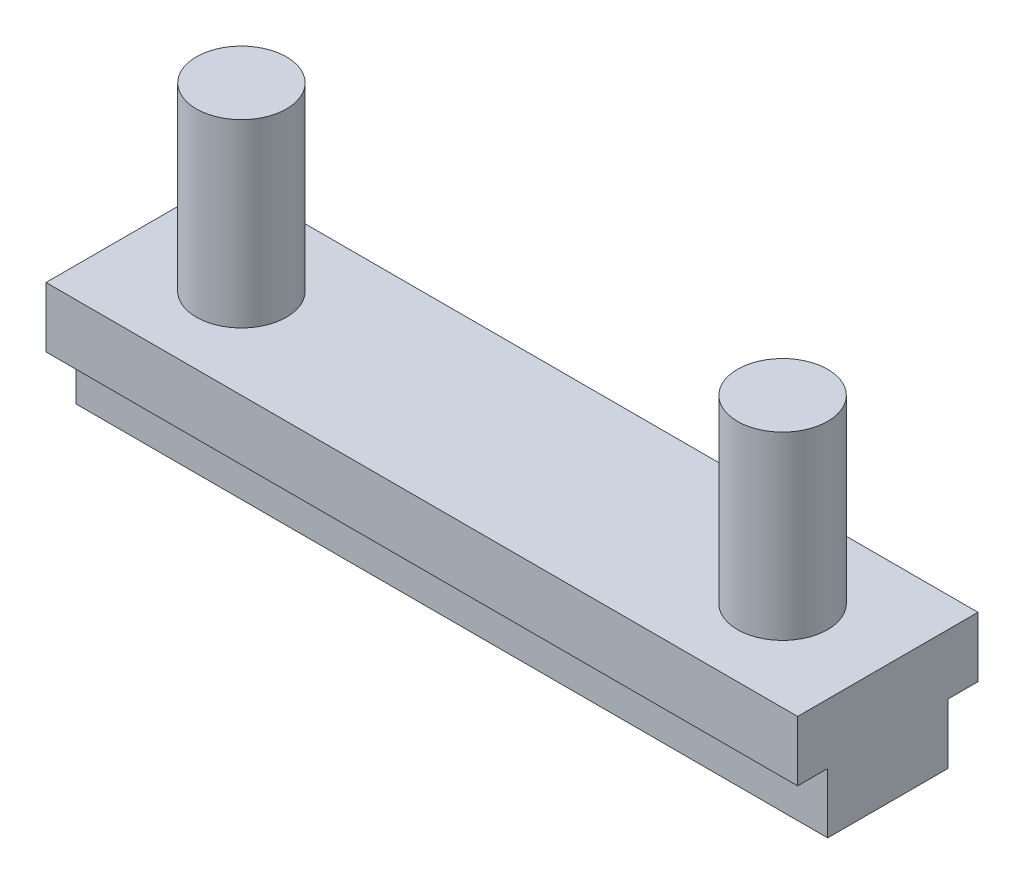
SolidWorks part; units mm, degrees
ref_plane "Front Plane" through (0, 0, 0) normal (0, 0, 1) x (1, 0, 0)
ref_plane "Top Plane" through (0, 0, 0) normal (0, 1, 0) x (1, 0, 0)
ref_plane "Right Plane" through (0, 0, 0) normal (1, 0, 0) x (0, 0, -1)
sketch "Sketch1" plane through (0, 0, 0) normal (0, 1, 0) x (1, 0, 0)
  line L1 (-62.5, -15) -> (62.5, -15)
  line L2 (-62.5, -15) -> (-62.5, 15)
  line L3 (-62.5, 15) -> (62.5, 15)
  line L4 (62.5, -15) -> (62.5, 15)
  line L5 (-62.5, -15) -> (62.5, 15) construction
  line L6 (-62.5, 15) -> (62.5, -15) construction
  circle A0 centre (-45, 0) radius 7.5
  circle A1 centre (45, 0) radius 7.5
  point P0 (0, 0)
  point P10 (0, 0)
  point P11 (0, 0)
  point P12 (0, 0)
  point P13 (0, 0)
  point P14 (42.5, 0)
  point P15 (0, 0)
  dimension "D4" = 15
  dimension "D1" = 90
  dimension "D2" = 125
  dimension "D3" = 30
  dimension "D5" = 15
  dimension "D6" = 45
extrude "Boss-Extrude1" add sketch "Sketch1" along normal blind 10
sketch "Sketch3" plane through (0, 0, 0) normal (0, -1, 0) x (1, 0, 0)
  line L0 (62.5, 15) -> (62.5, -15) construction
  line L1 (-62.5, -10) -> (62.5, -10)
  line L2 (-62.5, -10) -> (-62.5, 10)
  line L3 (-62.5, 10) -> (62.5, 10)
  line L4 (62.5, -10) -> (62.5, 10)
  line L5 (-62.5, -10) -> (62.5, 10) construction
  line L6 (-62.5, 10) -> (62.5, -10) construction
  point P0 (0, 0)
  dimension "D1" = 20
extrude "Boss-Extrude2" add sketch "Sketch3" along normal blind 10
sketch "Sketch4" plane through (0, 0, 0) normal (0, 1, 0) x (1, 0, 0)
  circle A0 centre (45, 0) radius 7.5 construction
  circle A1 centre (-45, 0) radius 7.5 construction
  circle A2 centre (45, 0) radius 7.5
  circle A3 centre (-45, 0) radius 7.5
extrude "Boss-Extrude3" add sketch "Sketch4" along normal blind 40
